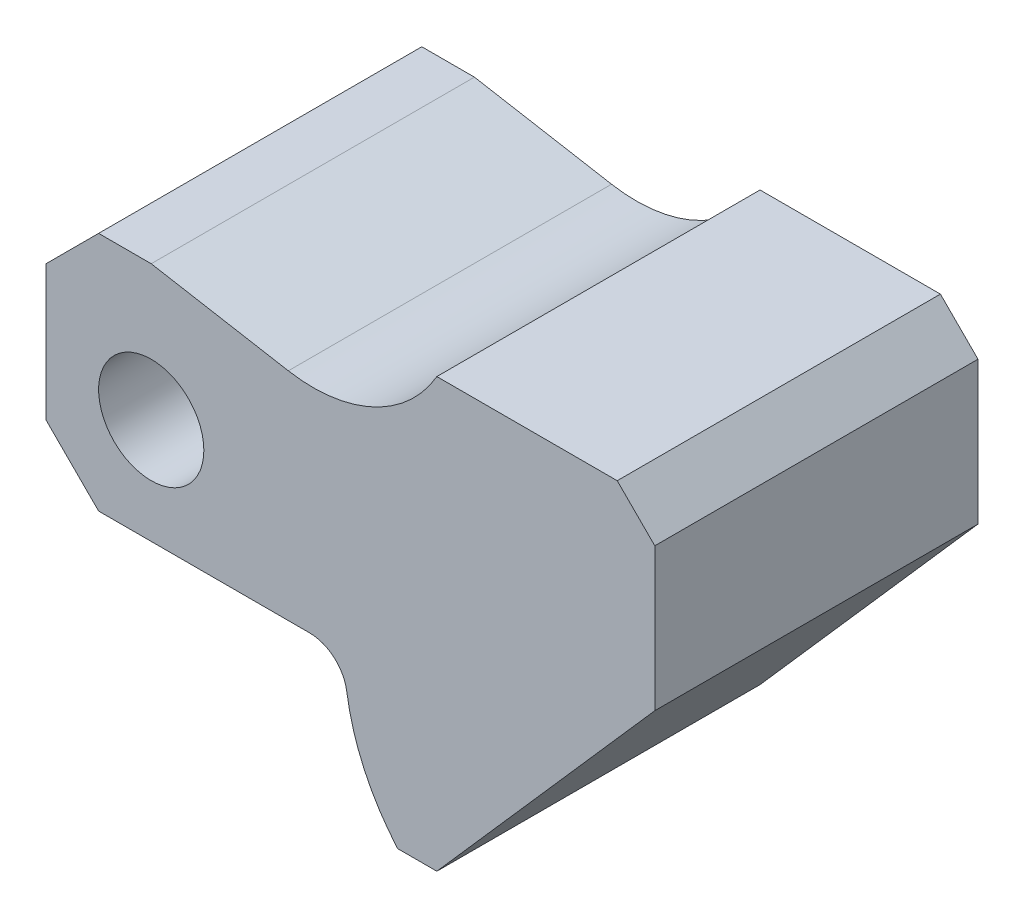
SolidWorks part; units mm, degrees
material "AISI 1020"
ref_plane "Plan de face" through (0, 0, 0) normal (0, 0, 1) x (1, 0, 0)
ref_plane "Plan de dessus" through (0, 0, 0) normal (0, 1, 0) x (1, 0, 0)
ref_plane "Plan de droite" through (0, 0, 0) normal (1, 0, 0) x (0, 0, -1)
sketch "Esquisse1" plane through (0, 0, 0) normal (0, 0, 1) x (1, 0, 0)
  line L0 (-14, 18) -> (0, 18)
  line L1 (67, -33) -> (-14, -33) construction
  line L2 (67, -33) -> (67, 24) construction
  line L3 (67, 24) -> (-14, 24) construction
  line L4 (-14, -33) -> (-14, 24) construction
  line L5 (0, 18) -> (18.2431, 14.7833)
  line L6 (38, 24) -> (62, 24)
  line L7 (62, 24) -> (67, 24)
  line L8 (67, 24) -> (67, 0)
  line L9 (67, 0) -> (38, -33)
  line L10 (38, -33) -> (32.7881, -33)
  line L12 (21.0666, -14) -> (-14, -14)
  line L13 (-14, -14) -> (-14, 18)
  circle A0 centre (0, 0) radius 7
  arc A1 (18.2431, 14.7833) -> (38, 24) centre (21.5424, 33.4946) ccw
  arc A2 (32.7881, -33) -> (26.0123, -18.2647) centre (54.697, -14) cw
  arc A3 (26.0123, -18.2647) -> (21.0666, -14) centre (21.0666, -19) ccw
  dimension "D7" = 32
  dimension "D13" = 5
  dimension "D14" = 29
  dimension "D9" = 19
  dimension "D18" = 14
  dimension "D1" = 81
  dimension "D2" = 57
  dimension "D3" = 29
  dimension "D4" = 24
  dimension "D5" = 14
  dimension "D6" = 14
  dimension "D8" = 19
  dimension "D12" = 10
  dimension "D15" = 29
  dimension "D16" = 14
  dimension "D17" = 19
extrude "Boss.-Extru.1" add sketch "Esquisse1" along normal blind 43
chamfer "Chanfrein1" distance 7 angle 45 2 edges at (-14, -14, 21.5) (-14, 18, 21.5)
chamfer "Chanfrein2" distance 5 angle 45 1 edges at (67, 24, 21.5)
equation "\"A\"= 81"
equation "\"B\"= 57"
equation "\"C\"= 43"
equation "\"D1@Boss.-Extru.1\"=\"C\""
